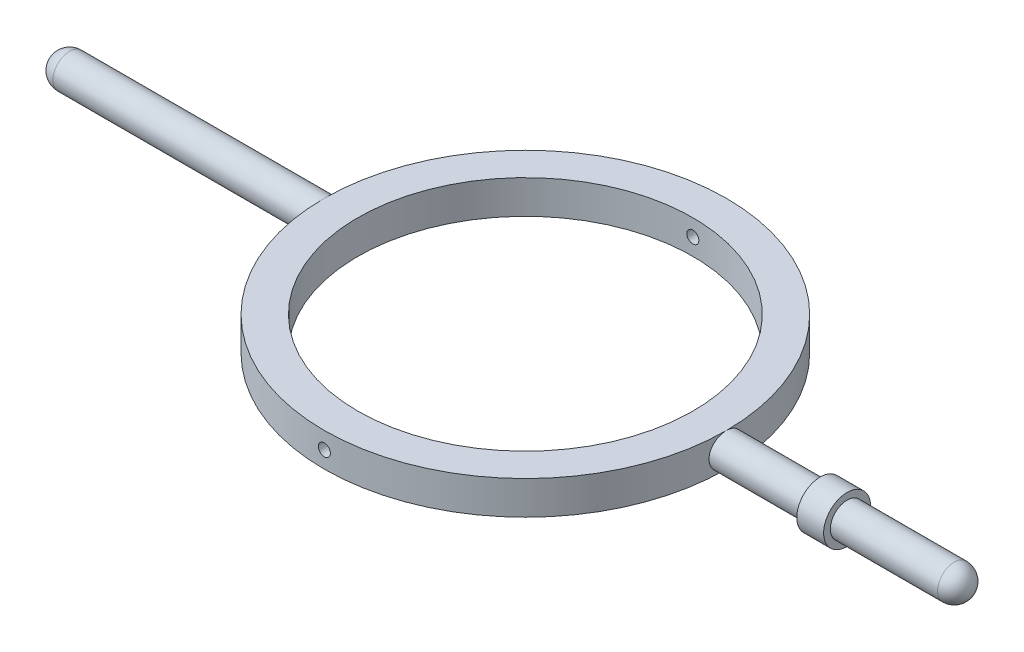
SolidWorks part; units mm, degrees
ref_plane "Front Plane" through (0, 0, 0) normal (0, 0, 1) x (1, 0, 0)
ref_plane "Top Plane" through (0, 0, 0) normal (0, 1, 0) x (1, 0, 0)
ref_plane "Right Plane" through (0, 0, 0) normal (1, 0, 0) x (0, 0, -1)
sketch "Sketch1" plane through (0, 0, 0) normal (0, 1, 0) x (1, 0, 0)
  circle A0 centre (0, 0) radius 12.5
  circle A1 centre (0, 0) radius 15
  dimension "D1" = 30
  dimension "D2" = 25
extrude "Boss-Extrude2" add sketch "Sketch1" along normal blind 2.5 contours A0 | A1
sketch "Sketch3" plane through (0, 0, 0) normal (0, 0, 1) x (1, 0, 0)
  circle A0 centre (0, 1.25) radius 0.45
  dimension "D1" = 1.25
  dimension "D2" = 0.9
extrude "Cut-Extrude2" cut sketch "Sketch3" against normal through all and the other way through all
ref_plane "Plane1" through (14, 0, 0) normal (1, 0, 0) x (0, 0, -1)
sketch "Sketch4" plane through (14, 0, 0) normal (1, 0, 0) x (0, 0, -1)
  line L0 (15, 2.5) -> (-15, 2.5) construction
  circle A0 centre (0, 1.25) radius 1.25
  dimension "D1" = 1.25
  dimension "D2" = 2.5
extrude "Boss-Extrude3" add sketch "Sketch4" along normal blind 18
sketch "Sketch5" plane through (32, 0, 0) normal (1, 0, 0) x (0, 0, -1)
  line L0 (0, 2.5) -> (0, 0)
  arc A0 (0, 0) -> (0, 2.5) centre (0, 1.25) ccw
revolve "Revolve1" add sketch "Sketch5" angle 360 about L0
ref_plane "Plane2" through (-14, 0, 0) normal (1, 0, 0) x (0, 0, -1)
sketch "Sketch6" plane through (-14, 0, 0) normal (1, 0, 0) x (0, 0, -1)
  line L0 (15, 2.5) -> (-15, 2.5) construction
  circle A0 centre (0, 1.25) radius 1.25
  dimension "D1" = 1.25
  dimension "D2" = 2.5
extrude "Boss-Extrude4" add sketch "Sketch6" against normal blind 20
sketch "Sketch7" plane through (-34, 0, 0) normal (-1, 0, 0) x (0, 0, 1)
  line L0 (0, 2.5) -> (0, 0)
  arc A0 (0, 0) -> (0, 2.5) centre (0, 1.25) ccw
  dimension "D1" = 1.25
revolve "Revolve2" add sketch "Sketch7" angle 360 about L0
ref_plane "Plane3" through (24, 0, 0) normal (1, 0, 0) x (0, 0, -1)
sketch "Sketch9" plane through (24, 0, 0) normal (1, 0, 0) x (0, 0, -1)
  circle A1 centre (0, 1.25) radius 1.75
  dimension "D1" = 3.5
extrude "Boss-Extrude5" add sketch "Sketch9" against normal blind 2
